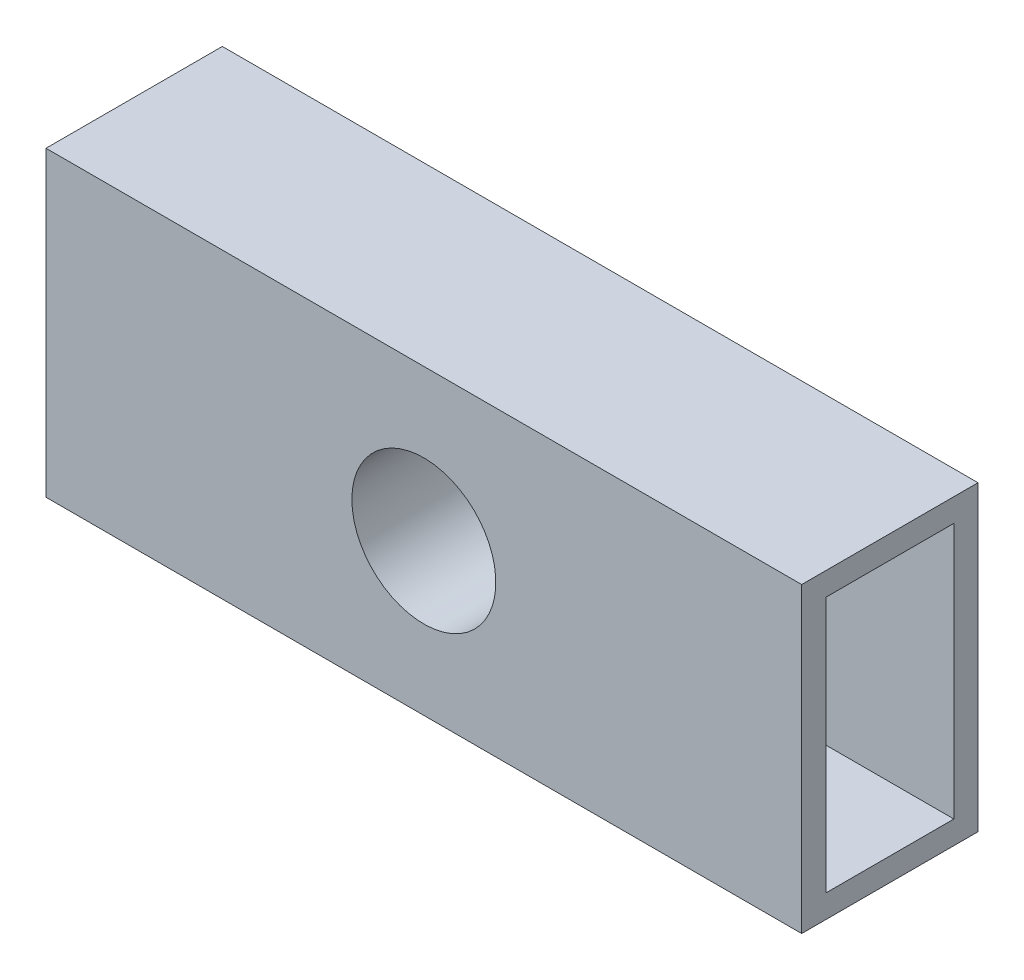
SolidWorks part; units mm, degrees
ref_plane "Front Plane" through (0, 0, 0) normal (0, 0, 1) x (1, 0, 0)
ref_plane "Top Plane" through (0, 0, 0) normal (0, 1, 0) x (1, 0, 0)
ref_plane "Right Plane" through (0, 0, 0) normal (1, 0, 0) x (0, 0, -1)
sketch "Sketch1" plane through (0, 0, 0) normal (0, 0, 1) x (1, 0, 0)
  line L1 (-75, -30) -> (75, -30)
  line L2 (-75, -30) -> (-75, 30)
  line L3 (-75, 30) -> (75, 30)
  line L4 (75, -30) -> (75, 30)
  line L5 (-75, -30) -> (75, 30) construction
  line L6 (-75, 30) -> (75, -30) construction
  point P0 (0, 0)
  dimension "D1" = 150
  dimension "D2" = 60
extrude "Boss-Extrude1" add sketch "Sketch1" along normal mid plane 35
sketch "Sketch2" plane through (75, 0, 0) normal (1, 0, 0) x (0, 0, -1)
  line L1 (-12.715, -25.415) -> (12.715, -25.415)
  line L2 (-12.715, -25.415) -> (-12.715, 25.415)
  line L3 (-12.715, 25.415) -> (12.715, 25.415)
  line L4 (12.715, -25.415) -> (12.715, 25.415)
  line L5 (-12.715, -25.415) -> (12.715, 25.415) construction
  line L6 (-12.715, 25.415) -> (12.715, -25.415) construction
  point P0 (0, 0)
  dimension "D1" = 50.83
  dimension "D2" = 25.43
extrude "Cut-Extrude1" cut sketch "Sketch2" against normal blind 50.8
sketch "Sketch3" plane through (0, 0, 0) normal (0, 0, 1) x (1, 0, 0)
  circle A0 centre (0, 0) radius 14.2875
  dimension "D1" = 28.575
extrude "Cut-Extrude2" cut sketch "Sketch3" along normal up to surface and the other way up to surface up to face at (0, 0, 17.5) other way up to face at (0, 0, -17.5)
mirror "Mirror1" about plane through (0, 0, 0) normal (1, 0, 0) of "Cut-Extrude1"
